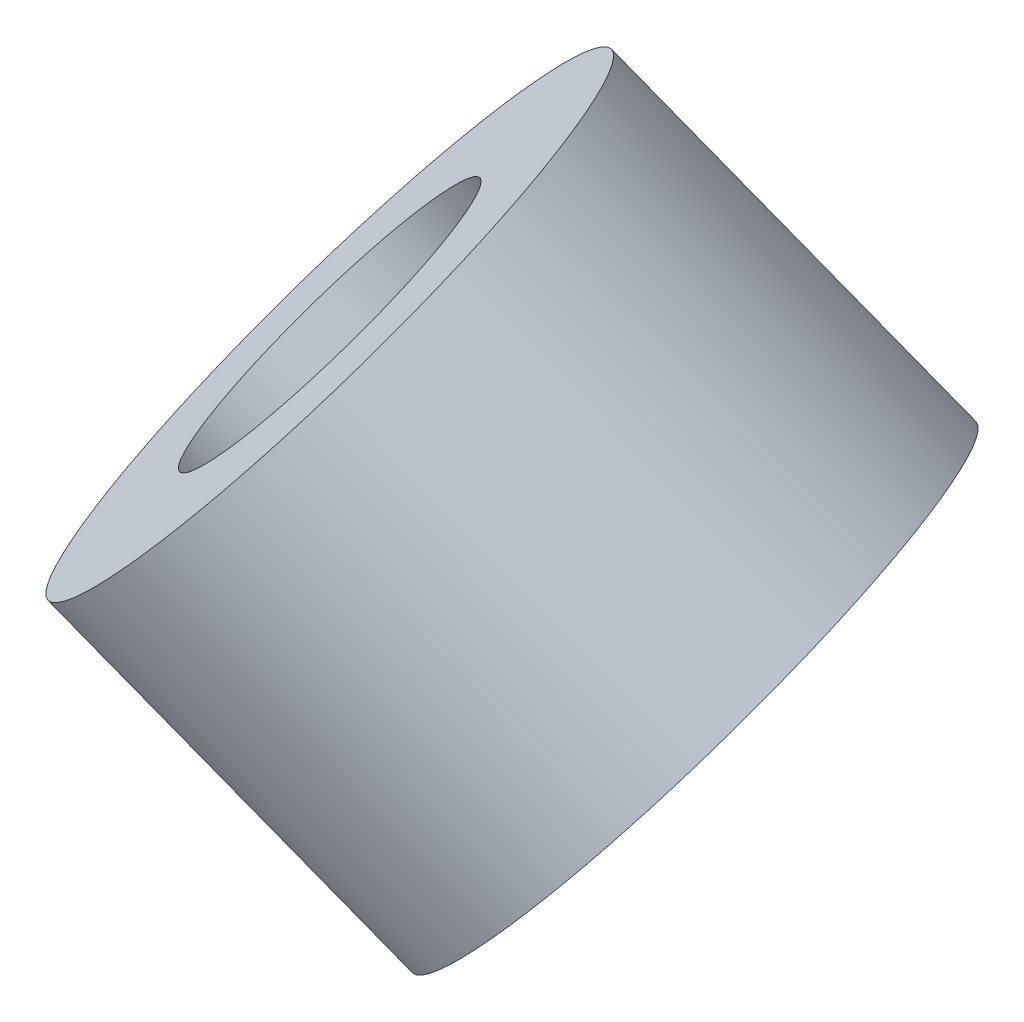
SolidWorks part; units mm, degrees
ref_plane "Front" through (0, 0, 0) normal (0, 0, 1) x (1, 0, 0)
ref_plane "Top" through (0, 0, 0) normal (0, 1, 0) x (1, 0, 0)
ref_plane "Right" through (0, 0, 0) normal (1, 0, 0) x (0, 0, -1)
sketch "Эскиз1" plane through (179.8397, -166.431, -70.2192) normal (-0.7055, 0.6529, 0.2755) x (0.6097, 0.3612, 0.7055)
  line L0 (3.1473, 60.175) -> (45.8867, 69.9394) construction
  circle A0 centre (24.517, 65.0572) radius 2
  circle A1 centre (24.517, 65.0572) radius 3.75
extrude "Бобышка-Вытянуть1" add sketch "Эскиз1" against normal blind 5
